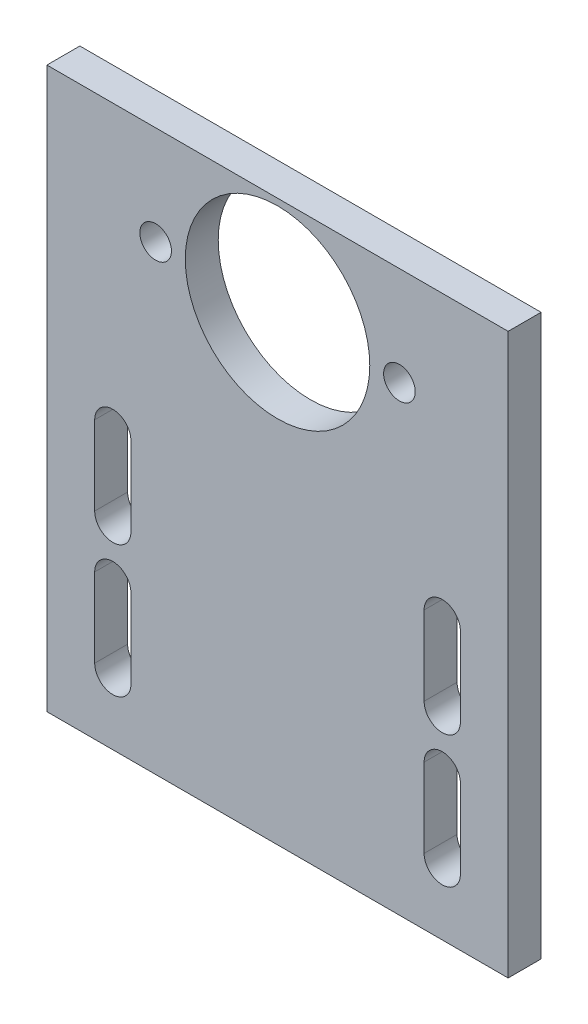
SolidWorks part; units mm, degrees
ref_plane "Front Plane" through (0, 0, 0) normal (0, 0, 1) x (1, 0, 0)
ref_plane "Top Plane" through (0, 0, 0) normal (0, 1, 0) x (1, 0, 0)
ref_plane "Right Plane" through (0, 0, 0) normal (1, 0, 0) x (0, 0, -1)
sketch "Sketch1" plane through (0, 0, 0) normal (0, 0, 1) x (1, 0, 0)
  line L0 (0, 0) -> (0, 100) construction
  line L1 (-35, -15) -> (35, -15) construction
  line L2 (-35, -15) -> (-35, 100)
  line L3 (-35, 100) -> (35, 100)
  line L4 (35, -15) -> (35, 100)
  line L5 (-35, -15) -> (35, 100) construction
  line L6 (-35, 100) -> (35, -15) construction
  line L7 (-18.5, 35) -> (18.5, 35) construction
  line L8 (0, 0) -> (0, -15) construction
  line L9 (-25, -5) -> (25, -5) construction
  line L10 (-35, -15) -> (-35, -35)
  line L11 (-25, -5) -> (-25, 7) construction
  line L12 (-35, -35) -> (35, -35)
  line L13 (35, -35) -> (35, -15)
  line L14 (-27.75, -5) -> (-27.75, 7)
  line L15 (-22.25, -5) -> (-22.25, 7)
  line L16 (25, -5) -> (25, 7) construction
  line L17 (27.75, -5) -> (27.75, 7)
  line L18 (22.25, -5) -> (22.25, 7)
  line L19 (-25, -25) -> (-25, -13) construction
  line L20 (-27.75, -25) -> (-27.75, -13)
  line L21 (-22.25, -25) -> (-22.25, -13)
  line L22 (25, -25) -> (25, -13) construction
  line L23 (27.75, -25) -> (27.75, -13)
  line L24 (22.25, -25) -> (22.25, -13)
  line L25 (-35, 50) -> (35, 50)
  circle A0 centre (-18.5, 35) radius 2.4
  circle A1 centre (18.5, 35) radius 2.4
  circle A2 centre (0, 35) radius 5
  circle A3 centre (-25, -5) radius 2.75 construction
  circle A4 centre (25, -5) radius 2.75 construction
  circle A5 centre (25, -25) radius 2.75 construction
  circle A6 centre (-25, -25) radius 2.75 construction
  circle A7 centre (0, 35) radius 14
  arc A8 (-27.75, -5) -> (-22.25, -5) centre (-25, -5) ccw
  arc A9 (-22.25, 7) -> (-27.75, 7) centre (-25, 7) ccw
  arc A10 (27.75, -5) -> (22.25, -5) centre (25, -5) cw
  arc A11 (22.25, 7) -> (27.75, 7) centre (25, 7) cw
  circle A12 centre (25, -5) radius 2.75 construction
  arc A13 (-27.75, -25) -> (-22.25, -25) centre (-25, -25) ccw
  arc A14 (-22.25, -13) -> (-27.75, -13) centre (-25, -13) ccw
  arc A15 (27.75, -25) -> (22.25, -25) centre (25, -25) cw
  arc A16 (22.25, -13) -> (27.75, -13) centre (25, -13) cw
  circle A17 centre (25, -25) radius 2.75 construction
  point P0 (0, 42.5)
  point P5 (-25, 1)
  point P10 (0, 35)
  point P18 (0, -5)
  point P34 (25, 1)
  point P41 (-25, -19)
  point P48 (25, -19)
  dimension "D4" = 4.8
  dimension "D5" = 10
  dimension "D6" = 5.5
  dimension "D11" = 28
  dimension "D14" = 2.75
  dimension "D15" = 2.75
  dimension "D1" = 70
  dimension "D2" = 115
  dimension "D3" = 37
  dimension "D7" = 10
  dimension "D8" = 65
  dimension "D9" = 10
  dimension "D10" = 20
  dimension "D12" = 10
  dimension "D13" = 12
  dimension "D16" = 12
  dimension "D17" = 50
extrude "Boss-Extrude1" add sketch "Sketch1" along normal blind 5 contours L25 L2 L10 L12 L13 L4 A14 L21 A13 L20 A9 L15 A8 L14 A7 A1 A0 L18 A11 L17 A10 L24 A16 L23 A15
